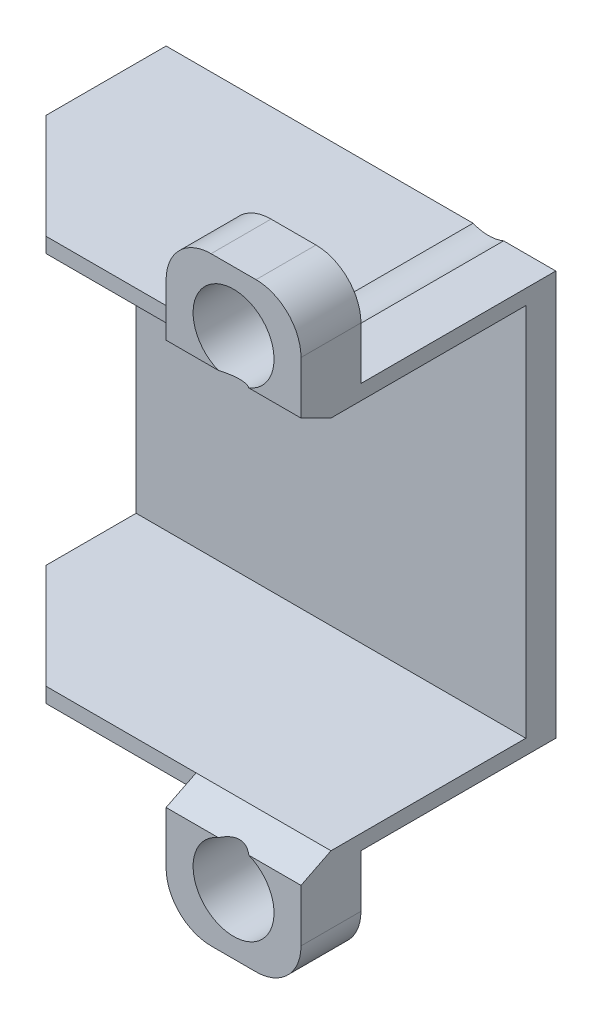
SolidWorks part; units mm, degrees
ref_plane "Alzado" through (0, 0, 0) normal (0, 0, 1) x (1, 0, 0)
ref_plane "Planta" through (0, 0, 0) normal (0, 1, 0) x (1, 0, 0)
ref_plane "Vista lateral" through (0, 0, 0) normal (1, 0, 0) x (0, 0, -1)
sketch "Croquis1" plane through (0, 0, 0) normal (0, 0, 1) x (1, 0, 0)
  line L1 (-39.3998, 10.6199) -> (-13.3998, 10.6199)
  line L2 (-39.3998, 10.6199) -> (-39.3998, -16.3801)
  line L3 (-39.3998, -16.3801) -> (-13.3998, -16.3801)
  line L4 (-13.3998, 10.6199) -> (-13.3998, -16.3801)
  dimension "D1" = 26
  dimension "D2" = 27
extrude "Saliente-Extruir1" add sketch "Croquis1" along normal blind 2
sketch "Croquis2" plane through (0, 0, 2) normal (0, 0, 1) x (1, 0, 0)
  line L0 (-13.3998, -16.3801) -> (-13.3998, 10.6199) construction
  line L2 (-39.3998, 10.6199) -> (-13.3998, 10.6199)
  line L3 (-39.3998, 10.6199) -> (-39.3998, 9.6199)
  line L4 (-39.3998, 9.6199) -> (-13.3998, 9.6199)
  line L5 (-13.3998, 10.6199) -> (-13.3998, 9.6199)
  line L7 (-39.3998, -16.3801) -> (-13.3998, -16.3801)
  line L8 (-39.3998, -16.3801) -> (-39.3998, -15.3801)
  line L9 (-39.3998, -15.3801) -> (-13.3998, -15.3801)
  line L10 (-13.3998, -16.3801) -> (-13.3998, -15.3801)
  dimension "D1" = 1
  dimension "D2" = 1
extrude "Saliente-Extruir2" add sketch "Croquis2" along normal blind 13
sketch "Croquis3" plane through (-13.3998, 0, 0) normal (1, 0, 0) x (0, 0, -1)
  line L0 (-17, -16.3801) -> (-15, -15.3801)
  line L1 (-15, -16.3801) -> (-13, -16.3801)
  line L3 (-15, -22.8801) -> (-13, -22.8801)
  line L4 (-13, -16.3801) -> (-13, -22.8801)
  line L5 (-15, 10.6199) -> (-13, 10.6199)
  line L7 (-15, 17.1199) -> (-13, 17.1199)
  line L8 (-13, 10.6199) -> (-13, 17.1199)
  line L11 (-15, -22.8801) -> (-17, -22.8801)
  line L12 (-17, -16.3801) -> (-17, -22.8801)
  line L15 (-15, 17.1199) -> (-17, 17.1199)
  line L16 (-17, 10.6199) -> (-17, 17.1199)
  line L17 (-15, -15.3801) -> (-15, -16.3801)
  line L18 (-17, 10.6199) -> (-15, 9.6199)
  line L19 (-15, 9.6199) -> (-15, 10.6199)
  dimension "D1" = 2
  dimension "D2" = 2
  dimension "D3" = 6.5
  dimension "D4" = 6.5
  dimension "D5" = 2
  dimension "D6" = 6.5
  dimension "D7" = 6.5
extrude "Saliente-Extruir3" add sketch "Croquis3" against normal blind 9
sketch "Croquis5" plane through (0, 0, 17) normal (0, 0, 1) x (1, 0, 0)
  line L0 (-22.3998, -22.8801) -> (-13.3998, -22.8801) construction
  line L2 (-22.3998, -16.3801) -> (-22.3998, -22.8801) construction
  line L3 (-22.3998, 17.1199) -> (-13.3998, 17.1199) construction
  line L4 (-22.3998, 17.1199) -> (-22.3998, 10.6199) construction
  circle A0 centre (-17.8998, -18.8801) radius 2.7
  circle A1 centre (-17.8998, 13.1199) radius 2.7
  dimension "D1" = 4
  dimension "D3" = 4
  dimension "D5" = 5.4
  dimension "D6" = 5.4
  dimension "D2" = 4.5
  dimension "D4" = 4.5
extrude "Cortar-Extruir1" cut sketch "Croquis5" against normal up to vertex (17 mm away) up to point (-39.3998, -16.3801, 0)
fillet "Redondeo1" radius 3 4 edges at (-22.3998, 17.1199, 15) (-13.3998, 17.1199, 15) (-22.3998, -22.8801, 15) (-13.3998, -22.8801, 15)
sketch "Croquis6" plane through (0, -16.3801, 0) normal (0, -1, 0) x (1, 0, 0)
  line L0 (-39.3998, 15) -> (-39.3998, 8)
  line L1 (-39.3998, 15) -> (-39.3998, 0) construction
  line L2 (-39.3998, 8) -> (-32.3998, 15)
  line L3 (-39.3998, 15) -> (-22.3998, 15) construction
  line L4 (-32.3998, 15) -> (-39.3998, 15)
  dimension "D1" = 7
  dimension "D2" = 7
extrude "Cortar-Extruir2" cut sketch "Croquis6" against normal up to vertex
